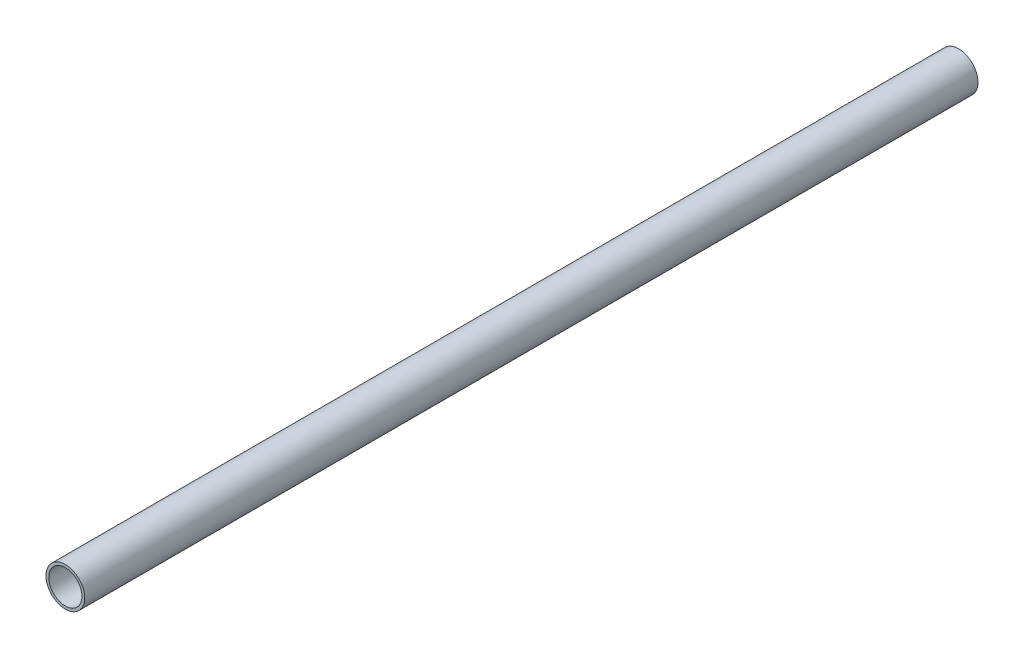
SolidWorks part; units mm, degrees
material "Thornel VCB-20 Carbon Cloth"
ref_plane "Front Plane" through (0, 0, 0) normal (0, 0, 1) x (1, 0, 0)
ref_plane "Top Plane" through (0, 0, 0) normal (0, 1, 0) x (1, 0, 0)
ref_plane "Right Plane" through (0, 0, 0) normal (1, 0, 0) x (0, 0, -1)
sketch "Sketch1" plane through (0, 0, 0) normal (0, 0, 1) x (1, 0, 0)
  circle A0 centre (0, 0) radius 9.525
  circle A1 centre (0, 0) radius 11.1125
  dimension "D1" = 19.05
  dimension "D2" = 22.225
extrude "Boss-Extrude1" add sketch "Sketch1" along normal mid plane 512.4704
